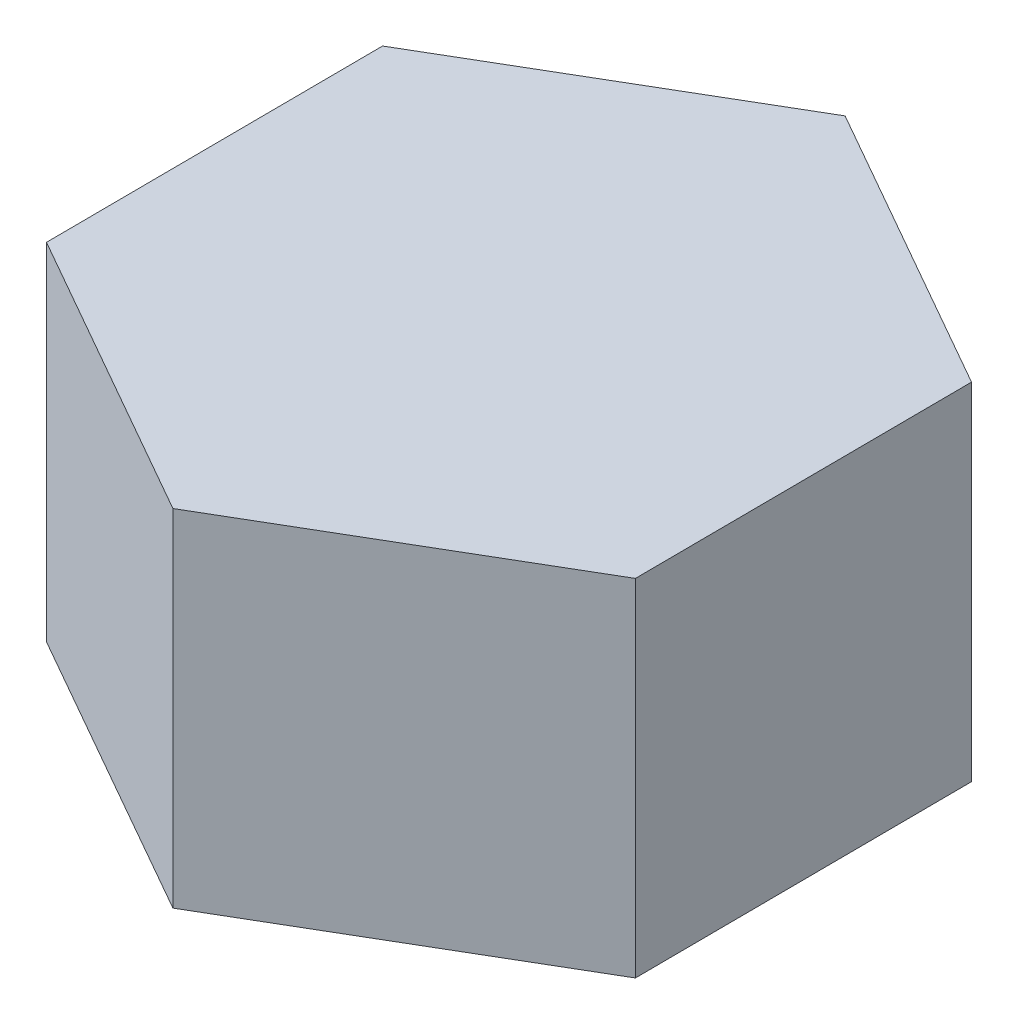
SolidWorks part; units mm, degrees
ref_plane "Front Plane" through (0, 0, 0) normal (0, 0, 1) x (1, 0, 0)
ref_plane "Top Plane" through (0, 0, 0) normal (0, 1, 0) x (1, 0, 0)
ref_plane "Right Plane" through (0, 0, 0) normal (1, 0, 0) x (0, 0, -1)
sketch "Sketch1" plane through (0, 0, 0) normal (0, 1, 0) x (1, 0, 0)
  line L1 (8.4883, -4.8351) -> (8.4314, 4.9335)
  line L2 (8.4314, 4.9335) -> (-0.0569, 9.7686)
  line L3 (-0.0569, 9.7686) -> (-8.4883, 4.8351)
  line L4 (-8.4883, 4.8351) -> (-8.4314, -4.9335)
  line L5 (-8.4314, -4.9335) -> (0.0569, -9.7686)
  line L6 (0.0569, -9.7686) -> (8.4883, -4.8351)
  circle A0 centre (0, 0) radius 8.46 construction
  dimension "D1" = 16.92
extrude "Boss-Extrude1" add sketch "Sketch1" along normal blind 10
